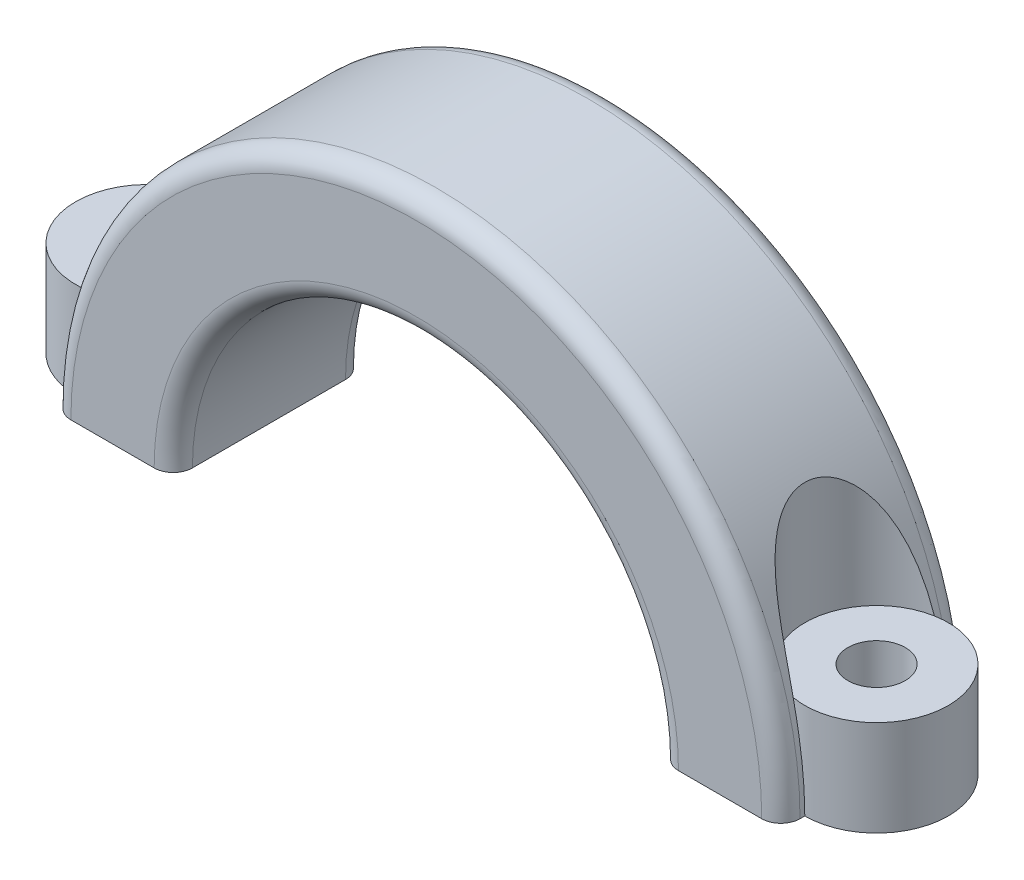
SolidWorks part; units mm, degrees
material "Chrome Stainless Steel"
ref_plane "Front Plane" through (0, 0, 0) normal (0, 0, 1) x (1, 0, 0)
ref_plane "Top Plane" through (0, 0, 0) normal (0, 1, 0) x (1, 0, 0)
ref_plane "Right Plane" through (0, 0, 0) normal (1, 0, 0) x (0, 0, -1)
sketch "Sketch1" plane through (0, 0, 0) normal (0, 0, 1) x (1, 0, 0)
  line L0 (-38.1, 0) -> (-25.4, 0)
  line L1 (25.4, 0) -> (38.1, 0)
  arc A0 (-25.4, 0) -> (25.4, 0) centre (0, 0) cw
  arc A1 (-38.1, 0) -> (38.1, 0) centre (0, 0) cw
  dimension "D1" = 25.4
  dimension "D2" = 38.1
extrude "Boss-Extrude1" add sketch "Sketch1" along normal mid plane 20
sketch "Sketch3" plane through (0, 0, 0) normal (0, -1, 0) x (1, 0, 0)
  line L0 (38.1, 10) -> (38.1, -10) construction
  circle A0 centre (38.1, 0) radius 7.5
  dimension "D1" = 15
extrude "Boss-Extrude2" add sketch "Sketch3" against normal blind 10
sketch "Sketch4" plane through (0, 0, 0) normal (0, -1, 0) x (1, 0, 0)
  circle A0 centre (38.1, 0) radius 3
  dimension "D1" = 6
extrude "Cut-Extrude1" cut sketch "Sketch4" against normal through all
sketch "Sketch5" plane through (0, 10, 0) normal (0, 1, 0) x (1, 0, 0)
  circle A0 centre (38.1, 0) radius 7.5
extrude "Cut-Extrude2" cut sketch "Sketch5" along normal through all
mirror "Mirror1" about plane through (0, 0, 0) normal (1, 0, 0) of "Boss-Extrude2", "Cut-Extrude1", "Cut-Extrude2"
fillet "Fillet1" radius 2 4 edges at (0, 25.4, 10) (0, 38.1, 10) (0, 25.4, -10) (0, 38.1, -10)
